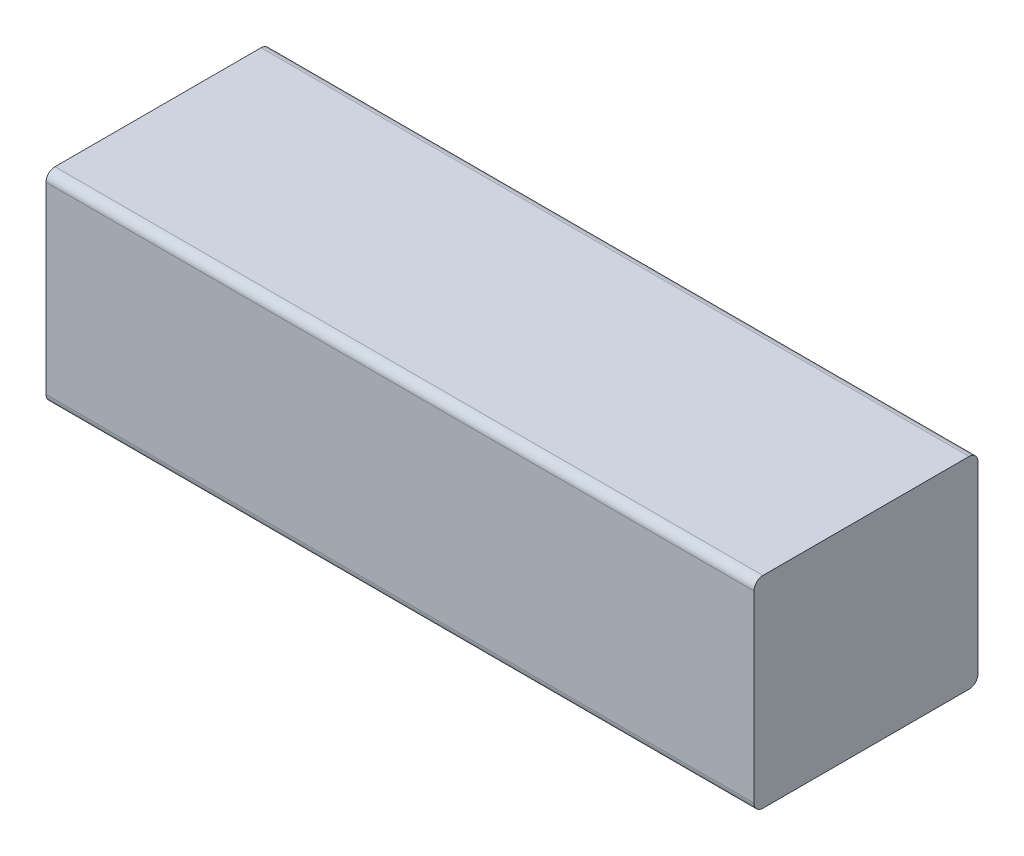
SolidWorks part; units mm, degrees
ref_plane "前视基准面" through (0, 0, 0) normal (0, 0, 1) x (1, 0, 0)
ref_plane "上视基准面" through (0, 0, 0) normal (0, 1, 0) x (1, 0, 0)
ref_plane "右视基准面" through (0, 0, 0) normal (1, 0, 0) x (0, 0, -1)
other "Configuration Table"
sketch "草图1" plane through (0, 0, 0) normal (0, 0, 1) x (1, 0, 0)
  line L1 (0, 0) -> (158, 0)
  line L2 (0, 0) -> (0, -45)
  line L3 (0, -45) -> (158, -45)
  line L4 (158, 0) -> (158, -45)
  dimension "D1" = 158
  dimension "D2" = 45
extrude "凸台-拉伸1" add sketch "草图1" along normal blind 50
fillet "圆角1" radius 2 4 edges at (79, -45, 0) (79, -45, 50) (79, 0, 0) (79, 0, 50)
